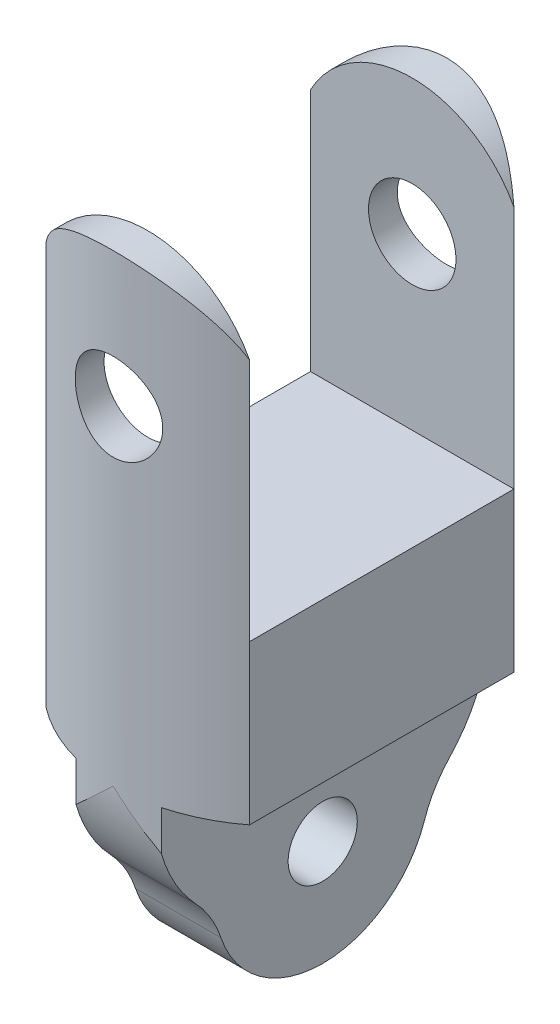
SolidWorks part; units mm, degrees
ref_plane "Front Plane" through (0, 0, 0) normal (0, 0, 1) x (1, 0, 0)
ref_plane "Top Plane" through (0, 0, 0) normal (0, 1, 0) x (1, 0, 0)
ref_plane "Right Plane" through (0, 0, 0) normal (1, 0, 0) x (0, 0, -1)
sketch "Sketch2" plane through (0, 0, 0) normal (0, 1, 0) x (1, 0, 0)
  circle A0 centre (0, 0) radius 4.1
  dimension "D1" = 8.2
extrude "Boss-Extrude1" add sketch "Sketch2" along normal blind 3.9
sketch "Sketch3" plane through (0, 3.9, 0) normal (0, 1, 0) x (1, 0, 0)
  line L0 (-2.5, 3.2496) -> (-2.5, -3.2496)
  line L1 (0, 0) -> (-4.7223, 0) construction
  line L2 (0, 4.7688) -> (0, -5.9046) construction
  line L3 (2.5, 3.2496) -> (2.5, -3.2496)
  circle A0 centre (0, 0) radius 4.1 construction
  arc A1 (-2.5, 3.2496) -> (-2.5, -3.2496) centre (0, 0) ccw
  arc A2 (2.5, 3.2496) -> (2.5, -3.2496) centre (0, 0) cw
  point P5 (-4.1, 0)
  point P8 (-4.1, 0)
  dimension "D1" = 1.6
extrude "Cut-Extrude1" cut sketch "Sketch3" against normal through all
sketch "Sketch4" plane through (0, 3.9, 0) normal (0, 1, 0) x (1, 0, 0)
  line L0 (-2.5, -3.2496) -> (2.5, -3.2496)
  line L1 (-2.5, -3.2496) -> (-2.5, 3.2496) construction
  line L2 (2.5, 3.2496) -> (2.5, -3.2496) construction
  line L3 (-3.3664, 0) -> (2.9996, 0) construction
  line L4 (-2.5, 3.2496) -> (2.5, 3.2496)
  arc A0 (-2.5, -3.2496) -> (2.5, -3.2496) centre (0, 0) ccw
  arc A1 (-2.5, 3.2496) -> (2.5, 3.2496) centre (0, 0) cw
  point P6 (0, -4.1)
  dimension "D1" = 0.8504
extrude "Boss-Extrude2" add sketch "Sketch4" along normal blind 7.5
ref_plane "Plane1" through (0, 0, 4.1) normal (0, 0, 1) x (1, 0, 0)
sketch "Sketch5" plane through (0, 0, 4.1) normal (0, 0, 1) x (1, 0, 0)
  line L0 (0, 11.7826) -> (0, -0.3371) construction
  line L1 (2.5, 11.4) -> (-2.5, 11.4) construction
  circle A0 centre (0, 8.075) radius 1.075
  point P5 (0, 7)
  dimension "D1" = 2.15
  dimension "D2" = 4.4
extrude "Cut-Extrude2" cut sketch "Sketch5" against normal through all and the other way through all
sketch "Sketch6" plane through (0, 0, 4.1) normal (0, 0, 1) x (1, 0, 0)
  line L0 (-2.5, 9.9) -> (-2.5, 11.4)
  line L1 (-2.5, 11.4) -> (-2.5, 3.9) construction
  line L2 (2.5, 11.4) -> (2.5, 9.9) construction
  line L3 (2.5, 11.4) -> (2.5, 3.9) construction
  line L4 (-2.5, 11.4) -> (0, 11.4)
  arc A0 (-2.5, 9.9) -> (0, 11.4) centre (0, 8.5667) cw
  dimension "D1" = 1.5
  dimension "D2" = 1.5
extrude "Cut-Extrude3" cut sketch "Sketch6" against normal through all
mirror "Mirror1" about plane through (0, 0, 0) normal (1, 0, 0) of "Cut-Extrude3"
sketch "Sketch7" plane through (0, 0, 0) normal (1, 0, 0) x (0, 0, -1)
  line L0 (0, 7.3615) -> (0, -7.2396) construction
  line L3 (-4.1, 2.75) -> (-4.1, -2.75) construction
  line L4 (-4.1, 3.5037) -> (-4.1, -4.4397) construction
  line L5 (4.1, 0) -> (-4.1, 0)
  line L6 (-4.1, 0) -> (-3.2496, 0) construction
  arc A0 (2.5021, -3.5) -> (-2.5021, -3.5) centre (0, -2.661) cw
  arc A1 (-2.5021, -3.5) -> (-3.1195, -2.4695) centre (-5.1568, -4.3902) ccw
  arc A2 (-3.1195, -2.4695) -> (-4.1, 0) centre (-0.5, 0) cw
  arc A3 (2.5021, -3.5) -> (3.1195, -2.4695) centre (5.1568, -4.3902) cw
  arc A4 (3.1195, -2.4695) -> (4.1, 0) centre (0.5, 0) ccw
  point P6 (0, -5.3)
  dimension "D3" = 3.6
  dimension "D4" = 2.8
  dimension "D1" = 3.5
  dimension "D2" = 5.3
extrude "Boss-Extrude3" add sketch "Sketch7" along normal mid plane 2.1
sketch "Sketch8" plane through (0, 0, 0) normal (0, 1, 0) x (1, 0, 0)
  line L0 (-1.05, -3.9633) -> (-1.05, -4.1)
  line L1 (-2.75, -4.1) -> (2.75, -4.1) construction
  line L2 (-1.05, -3.9633) -> (-1.05, -4.1) construction
  line L3 (-1.05, -4.1) -> (0, -4.1)
  line L5 (-3.4356, 0) -> (4.983, 0) construction
  line L6 (-1.05, 4.1) -> (0, 4.1)
  line L7 (-1.05, 3.9633) -> (-1.05, 4.1)
  arc A0 (-1.05, -3.9633) -> (0, -4.1) centre (0, 0) ccw
  arc A1 (-1.05, 3.9633) -> (0, 4.1) centre (0, 0) cw
  dimension "D1" = 4.1
extrude "Cut-Extrude4" cut sketch "Sketch8" against normal through all
mirror "Mirror2" about plane through (0, 0, 0) normal (1, 0, 0) of "Cut-Extrude4"
sketch "Sketch9" plane through (1.05, 0, 0) normal (1, 0, 0) x (0, 0, -1)
  line L0 (0, 1.9586) -> (0, -6.1559) construction
  circle A0 centre (0, -2.7) radius 0.85
  arc A1 (-2.5021, -3.5) -> (2.5021, -3.5) centre (0, -2.661) ccw construction
  point P5 (0, -1.85)
  point P6 (0, -5.3)
  dimension "D1" = 1.7
  dimension "D2" = 3.45
extrude "Cut-Extrude5" cut sketch "Sketch9" against normal up to next
